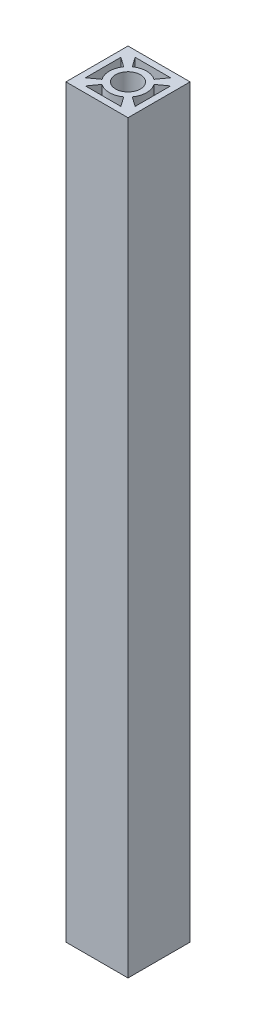
SolidWorks part; units mm, degrees
ref_plane "Front Plane" through (0, 0, 0) normal (0, 0, 1) x (1, 0, 0)
ref_plane "Top Plane" through (0, 0, 0) normal (0, 1, 0) x (1, 0, 0)
ref_plane "Right Plane" through (0, 0, 0) normal (1, 0, 0) x (0, 0, -1)
sketch "Sketch1" plane through (0, 0, 0) normal (0, 0, 1) x (1, 0, 0)
  line L1 (-50, 600) -> (50, 600)
  line L2 (-50, 600) -> (-50, -600)
  line L3 (-50, -600) -> (50, -600)
  line L4 (50, 600) -> (50, -600)
  line L5 (-50, 600) -> (50, -600) construction
  line L6 (-50, -600) -> (50, 600) construction
  point P0 (0, 0)
  dimension "D1" = 1200
  dimension "D2" = 100
extrude "Boss-Extrude1" add sketch "Sketch1" along normal blind 100
sketch "Sketch2" plane through (0, 600, 0) normal (0, 1, 0) x (1, 0, 0)
  line L10 (50, 0) -> (-50, 0) construction
  line L11 (-40, -21.4259) -> (-24.4112, -32.5618)
  line L12 (-14.1421, -35.8579) -> (0, -50) construction
  line L13 (50, -100) -> (50, 0) construction
  line L14 (-40, -90) -> (40, -90)
  line L15 (40, -90) -> (40, -10)
  line L16 (-40, -10) -> (-40, -90)
  line L17 (40, -10) -> (-40, -10)
  line L20 (-40, -21.4259) -> (-40, -78.5741)
  line L27 (-40, -78.5741) -> (-24.4112, -67.4382)
  arc A0 (-24.4112, -32.5618) -> (-17.4382, -25.5888) centre (0, -50) ccw
  circle A1 centre (0, -50) radius 20
  circle A2 centre (0, -50) radius 30 construction
  point P31 (0, -50)
  dimension "D3" = 60
  dimension "D2" = 50
  dimension "D5" = 50
  dimension "D1" = 10
  dimension "D4" = 10
sketch "Sketch3" plane through (0, 600, 0) normal (0, 1, 0) x (1, 0, 0)
  line L0 (-24.4112, -67.4382) -> (-40, -78.5741)
  line L1 (-40, -78.5741) -> (-40, -21.4259)
  line L2 (-40, -21.4259) -> (-24.4112, -32.5618)
  line L3 (-17.4382, -25.5888) -> (-28.5741, -10)
  line L4 (-28.5741, -10) -> (28.5741, -10)
  line L5 (28.5741, -10) -> (17.4382, -25.5888)
  line L6 (24.4112, -32.5618) -> (40, -21.4259)
  line L7 (40, -21.4259) -> (40, -78.5741)
  line L8 (40, -78.5741) -> (24.4112, -67.4382)
  line L9 (17.4382, -74.4112) -> (28.5741, -90)
  line L10 (28.5741, -90) -> (-28.5741, -90)
  line L11 (-28.5741, -90) -> (-17.4382, -74.4112)
  arc A0 (-24.4112, -32.5618) -> (-24.4112, -67.4382) centre (0, -50) ccw
  circle A1 centre (0, -50) radius 20
  arc A2 (17.4382, -25.5888) -> (-17.4382, -25.5888) centre (0, -50) ccw
  arc A3 (24.4112, -67.4382) -> (24.4112, -32.5618) centre (0, -50) ccw
  arc A4 (-17.4382, -74.4112) -> (17.4382, -74.4112) centre (0, -50) ccw
  point P26 (0, -50)
  dimension "D1" = 4
extrude "Cut-Extrude1" cut sketch "Sketch3" against normal through all
